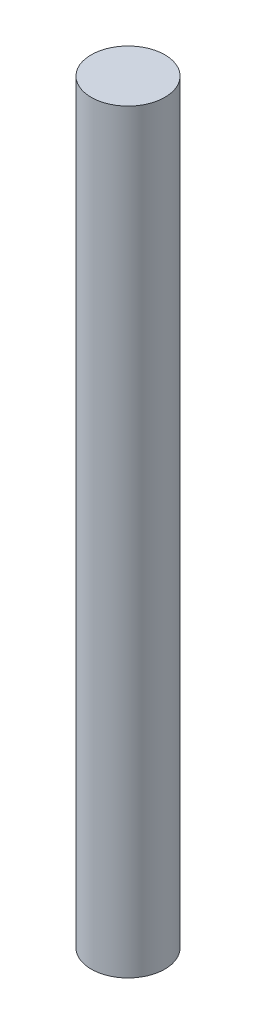
SolidWorks part; units mm, degrees
ref_plane "Спереди" through (0, 0, 0) normal (0, 0, 1) x (1, 0, 0)
ref_plane "Сверху" through (0, 0, 0) normal (0, 1, 0) x (1, 0, 0)
ref_plane "Справа" through (0, 0, 0) normal (1, 0, 0) x (0, 0, -1)
sketch "Эскиз1" plane through (0, 0, 0) normal (0, 1, 0) x (1, 0, 0)
  circle A0 centre (0, 0) radius 10
extrude "Бобышка-Вытянуть1" add sketch "Эскиз1" along normal blind 205
